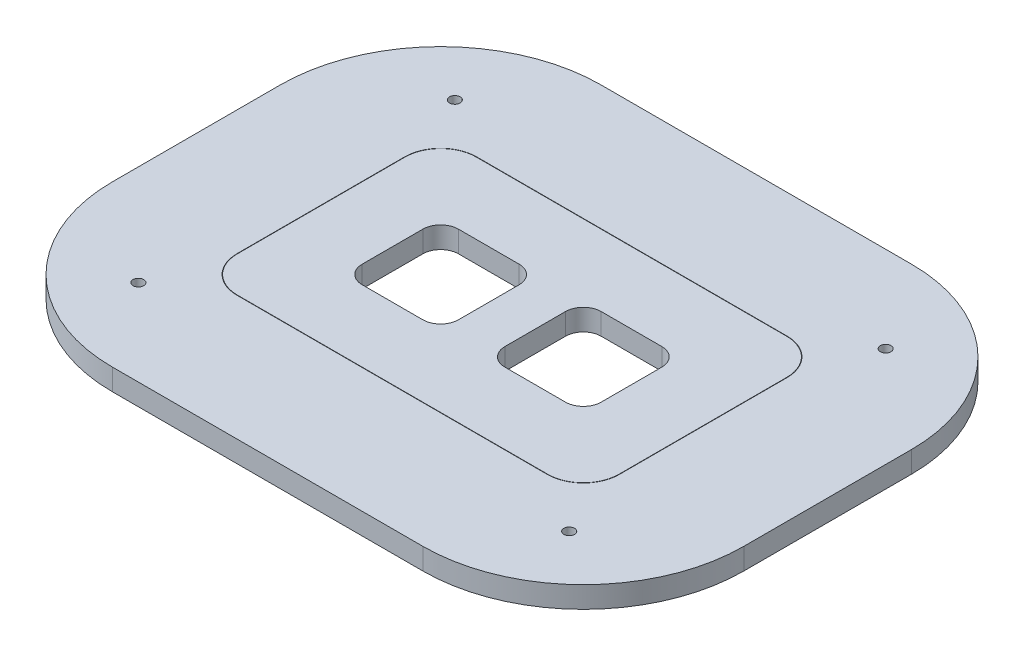
SolidWorks part; units mm, degrees
ref_plane "Front Plane" through (0, 0, 0) normal (0, 0, 1) x (1, 0, 0)
ref_plane "Top Plane" through (0, 0, 0) normal (0, 1, 0) x (1, 0, 0)
ref_plane "Right Plane" through (0, 0, 0) normal (1, 0, 0) x (0, 0, -1)
sketch "Sketch1" plane through (0, 0, 0) normal (0, 1, 0) x (1, 0, 0)
  line L0 (-20, 0) -> (0, 0) construction
  line L1 (-43.5, -33.5) -> (43.5, -33.5)
  line L2 (-53.5, -23.5) -> (-53.5, 23.5)
  line L3 (-43.5, 33.5) -> (43.5, 33.5)
  line L4 (53.5, -23.5) -> (53.5, 23.5)
  line L5 (-53.5, -33.5) -> (53.5, 33.5) construction
  line L6 (-53.5, 33.5) -> (53.5, -33.5) construction
  line L7 (-28.5, -13.5) -> (-11.5, -13.5)
  line L8 (-33.5, -8.5) -> (-33.5, 8.5)
  line L9 (-28.5, 13.5) -> (-11.5, 13.5)
  line L10 (-6.5, -8.5) -> (-6.5, 8.5)
  line L11 (-33.5, -13.5) -> (-6.5, 13.5) construction
  line L12 (-33.5, 13.5) -> (-6.5, -13.5) construction
  line L13 (11.5, -13.5) -> (28.5, -13.5)
  line L14 (6.5, -8.5) -> (6.5, 8.5)
  line L15 (11.5, 13.5) -> (28.5, 13.5)
  line L16 (33.5, -8.5) -> (33.5, 8.5)
  line L17 (6.5, -13.5) -> (33.5, 13.5) construction
  line L18 (6.5, 13.5) -> (33.5, -13.5) construction
  line L19 (0, 0) -> (20, 0) construction
  arc A0 (28.5, -13.5) -> (33.5, -8.5) centre (28.5, -8.5) ccw
  arc A1 (28.5, 13.5) -> (33.5, 8.5) centre (28.5, 8.5) cw
  arc A2 (6.5, 8.5) -> (11.5, 13.5) centre (11.5, 8.5) cw
  arc A3 (-28.5, -13.5) -> (-33.5, -8.5) centre (-28.5, -8.5) cw
  arc A4 (-11.5, -13.5) -> (-6.5, -8.5) centre (-11.5, -8.5) ccw
  arc A5 (-11.5, 13.5) -> (-6.5, 8.5) centre (-11.5, 8.5) cw
  arc A6 (-33.5, 8.5) -> (-28.5, 13.5) centre (-28.5, 8.5) cw
  arc A7 (11.5, -13.5) -> (6.5, -8.5) centre (11.5, -8.5) cw
  arc A8 (-43.5, -33.5) -> (-53.5, -23.5) centre (-43.5, -23.5) cw
  arc A9 (43.5, -33.5) -> (53.5, -23.5) centre (43.5, -23.5) ccw
  arc A10 (43.5, 33.5) -> (53.5, 23.5) centre (43.5, 23.5) cw
  arc A11 (-53.5, 23.5) -> (-43.5, 33.5) centre (-43.5, 23.5) cw
  point P0 (0, 0)
  point P6 (-20, 0)
  point P11 (20, 0)
  point P19 (0, 0)
  dimension "D3" = 5
  dimension "D4" = 5
  dimension "D7" = 10
  dimension "D1" = 27
  dimension "D2" = 20
  dimension "D5" = 20
  dimension "D6" = 20
extrude "Boss-Extrude1" add sketch "Sketch1" along normal blind 6
sketch "Sketch2" plane through (0, 6, 0) normal (0, 1, 0) x (1, 0, 0)
  line L0 (-75.3198, 55.3198) -> (75.3198, -55.3198) construction
  line L1 (75.3198, 55.3198) -> (-75.3198, -55.3198) construction
  line L2 (0, 0) -> (0, 25.0353) construction
  line L3 (0, 0) -> (38.8357, 0) construction
  line L8 (-43.5, -33.6) -> (43.5, -33.6)
  line L9 (53.6, -23.5) -> (53.6, 23.5)
  line L10 (43.5, 33.6) -> (-43.5, 33.6)
  line L11 (-53.6, 23.5) -> (-53.6, -23.5)
  line L12 (-43.5, -33.6) -> (43.5, -33.6)
  line L13 (53.6, -23.5) -> (53.6, 23.5)
  line L14 (43.5, 33.6) -> (-43.5, 33.6)
  line L15 (-53.6, 23.5) -> (-53.6, -23.5)
  line L20 (-43.5, -68.5) -> (43.5, -68.5)
  line L21 (88.5, -23.5) -> (88.5, 23.5)
  line L22 (43.5, 68.5) -> (-43.5, 68.5)
  line L23 (-88.5, 23.5) -> (-88.5, -23.5)
  line L24 (-43.5, -68.5) -> (43.5, -68.5)
  line L25 (88.5, -23.5) -> (88.5, 23.5)
  line L26 (43.5, 68.5) -> (-43.5, 68.5)
  line L27 (-88.5, 23.5) -> (-88.5, -23.5)
  circle A0 centre (-60.391, 44.3551) radius 1.5
  circle A1 centre (60.391, 44.3551) radius 1.5
  circle A2 centre (-60.391, -44.3551) radius 1.5
  circle A3 centre (60.391, -44.3551) radius 1.5
  arc A8 (-53.6, -23.5) -> (-43.5, -33.6) centre (-43.5, -23.5) ccw
  arc A9 (43.5, -33.6) -> (53.6, -23.5) centre (43.5, -23.5) ccw
  arc A10 (53.6, 23.5) -> (43.5, 33.6) centre (43.5, 23.5) ccw
  arc A11 (-43.5, 33.6) -> (-53.6, 23.5) centre (-43.5, 23.5) ccw
  arc A12 (-53.6, -23.5) -> (-43.5, -33.6) centre (-43.5, -23.5) ccw
  arc A13 (43.5, -33.6) -> (53.6, -23.5) centre (43.5, -23.5) ccw
  arc A14 (53.6, 23.5) -> (43.5, 33.6) centre (43.5, 23.5) ccw
  arc A15 (-43.5, 33.6) -> (-53.6, 23.5) centre (-43.5, 23.5) ccw
  arc A20 (-88.5, -23.5) -> (-43.5, -68.5) centre (-43.5, -23.5) ccw
  arc A21 (43.5, -68.5) -> (88.5, -23.5) centre (43.5, -23.5) ccw
  arc A22 (88.5, 23.5) -> (43.5, 68.5) centre (43.5, 23.5) ccw
  arc A23 (-43.5, 68.5) -> (-88.5, 23.5) centre (-43.5, 23.5) ccw
  arc A24 (-88.5, -23.5) -> (-43.5, -68.5) centre (-43.5, -23.5) ccw
  arc A25 (43.5, -68.5) -> (88.5, -23.5) centre (43.5, -23.5) ccw
  arc A26 (88.5, 23.5) -> (43.5, 68.5) centre (43.5, 23.5) ccw
  arc A27 (-43.5, 68.5) -> (-88.5, 23.5) centre (-43.5, 23.5) ccw
  point P9 (-45.4806, 33.4039)
  dimension "D3" = 18.5
  dimension "D4" = 3
  dimension "D1" = 0.1
  dimension "D2" = 35
extrude "Boss-Extrude2" add sketch "Sketch2" against normal blind 6 separate body
